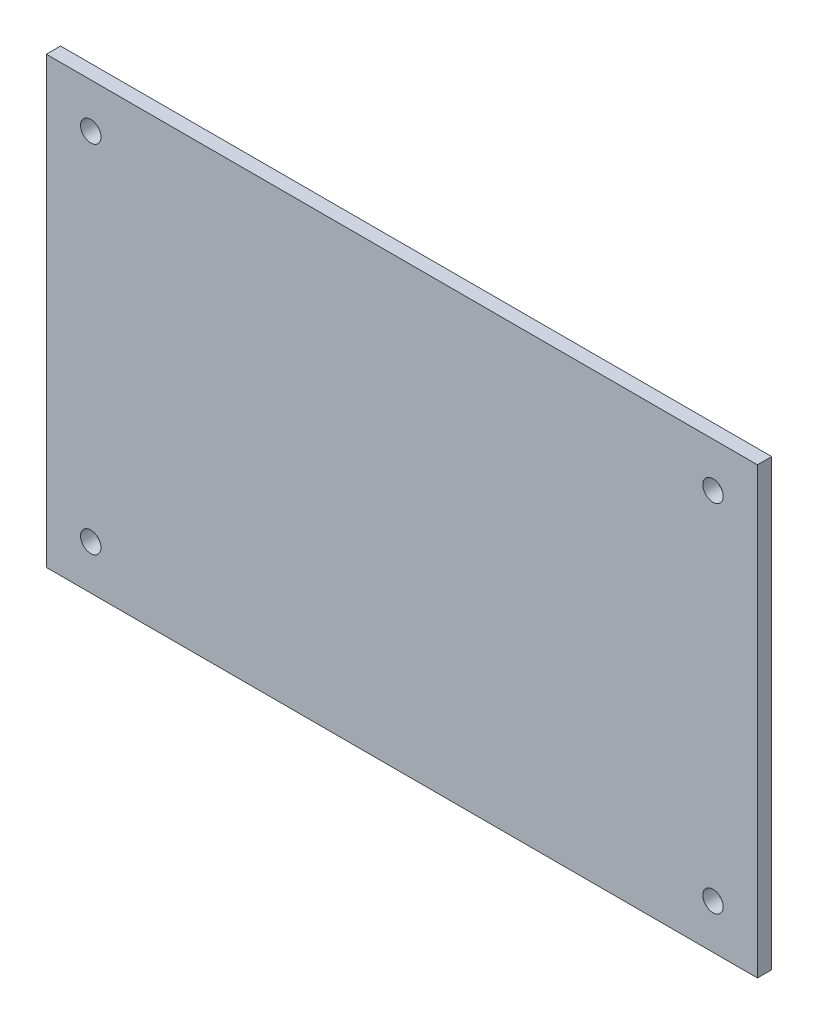
SolidWorks part; units mm, degrees
ref_plane "Front Plane" through (0, 0, 0) normal (0, 0, 1) x (1, 0, 0)
ref_plane "Top Plane" through (0, 0, 0) normal (0, 1, 0) x (1, 0, 0)
ref_plane "Right Plane" through (0, 0, 0) normal (1, 0, 0) x (0, 0, -1)
sketch "Sketch1" plane through (0, 0, 0) normal (0, 0, 1) x (1, 0, 0)
  line L1 (-40, -25) -> (40, -25)
  line L2 (-40, -25) -> (-40, 25)
  line L3 (-40, 25) -> (40, 25)
  line L4 (40, -25) -> (40, 25)
  line L5 (-40, -25) -> (40, 25) construction
  line L6 (-40, 25) -> (40, -25) construction
  circle A0 centre (-35, 20) radius 1.15
  circle A1 centre (-35, -20) radius 1.15
  circle A2 centre (35, 20) radius 1.15
  circle A3 centre (35, -20) radius 1.15
  point P0 (0, 0)
  point P14 (0, 0)
  point P15 (0, 0)
  point P16 (0, 0)
  point P17 (0, 0)
  point P18 (0, 0)
  point P19 (0, 0)
  dimension "D7" = 2.3
  dimension "D1" = 50
  dimension "D2" = 80
  dimension "D3" = 5
  dimension "D4" = 5
  dimension "D5" = 5
  dimension "D6" = 5
extrude "Boss-Extrude1" add sketch "Sketch1" along normal blind 1.6
equation "\"D4@Sketch1\"=\"D3@Sketch1\""
equation "\"D6@Sketch1\"=\"D5@Sketch1\""
